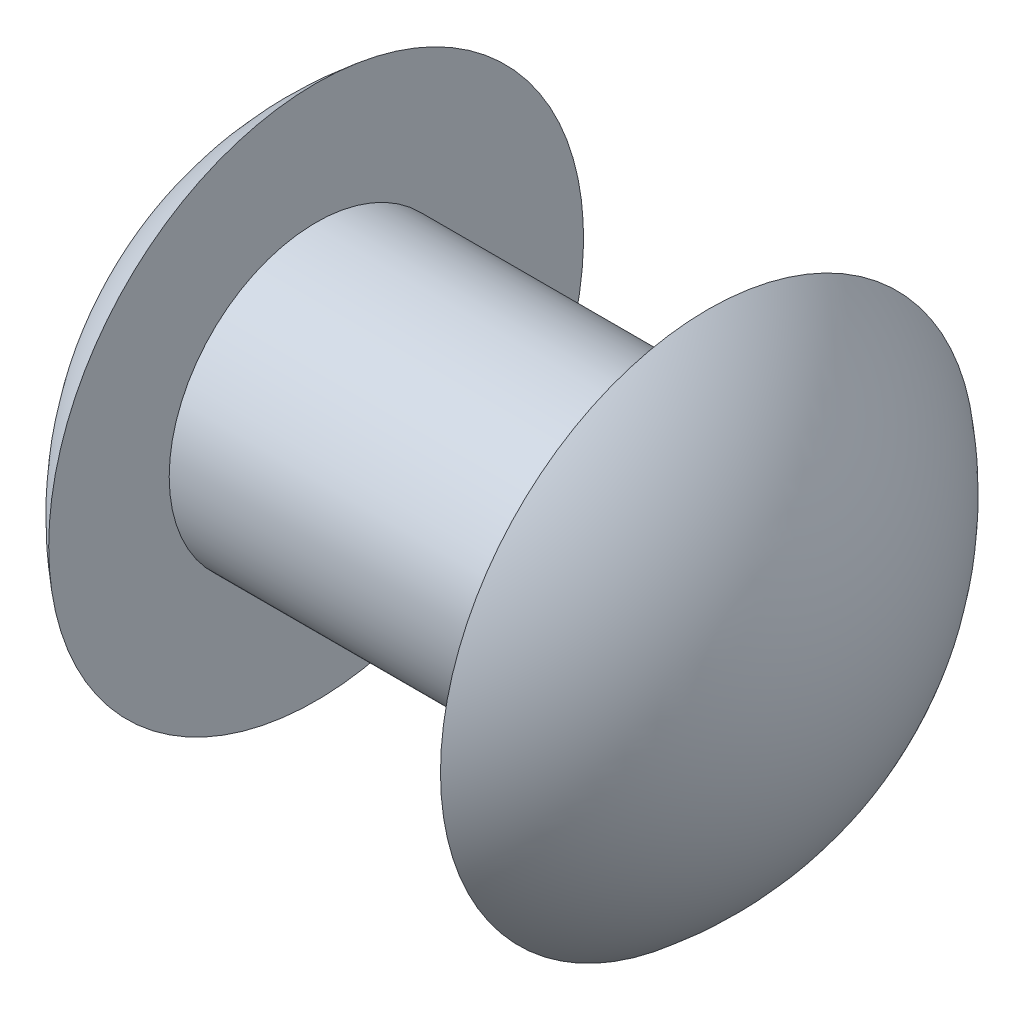
SolidWorks part; units mm, degrees
ref_plane "Спереди" through (0, 0, 0) normal (0, 0, 1) x (1, 0, 0)
ref_plane "Сверху" through (0, 0, 0) normal (0, 1, 0) x (1, 0, 0)
ref_plane "Справа" through (0, 0, 0) normal (1, 0, 0) x (0, 0, -1)
sketch "Эскиз1" plane through (0, 0, 0) normal (0, 0, 1) x (1, 0, 0)
  line L0 (-49.4235, 0) -> (69.1358, 0) construction
  line L1 (-0.0177, 1.5) -> (-0.0177, 2.7303)
  line L2 (-1.3278, 0) -> (5.2924, 0)
  line L3 (3.9823, 1.5) -> (3.9823, 2.7303)
  line L4 (-0.0177, 1.5) -> (3.9823, 1.5)
  arc A0 (-0.0177, 2.7303) -> (-1.3278, 0) centre (2.1722, 0) ccw
  arc A1 (3.9823, 2.7303) -> (5.2924, 0) centre (1.7924, 0) cw
  dimension "D2" = 3.5
  dimension "D1" = 4
  dimension "D3" = 1.5
revolve "Повернуть1" add sketch "Эскиз1" angle 360 about L0
